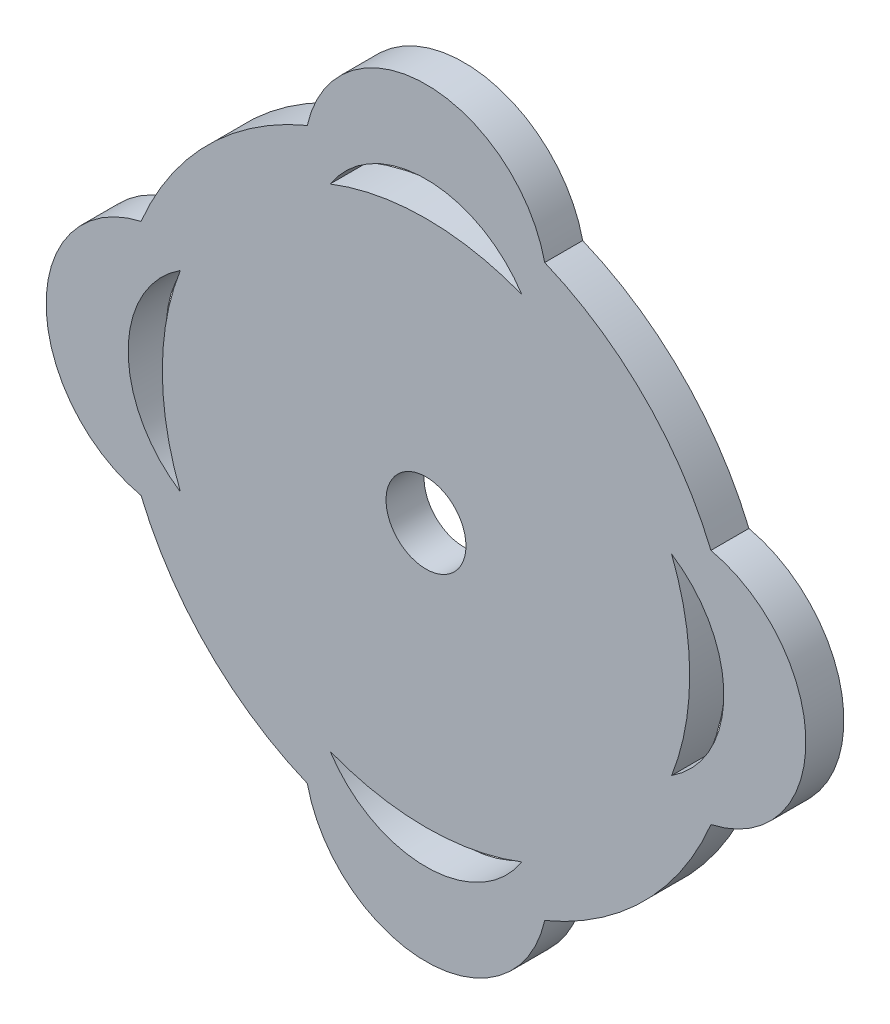
SolidWorks part; units mm, degrees
material "PLA"
ref_plane "Front Plane" through (0, 0, 0) normal (0, 0, 1) x (1, 0, 0)
ref_plane "Top Plane" through (0, 0, 0) normal (0, 1, 0) x (1, 0, 0)
ref_plane "Right Plane" through (0, 0, 0) normal (1, 0, 0) x (0, 0, -1)
sketch "Sketch1" plane through (0, 0, 0) normal (0, 0, 1) x (1, 0, 0)
  arc A0 (-3.175, -7.62) -> (3.175, -7.62) centre (0, -6.9056) ccw
  arc A1 (-7.62, 3.175) -> (-7.62, -3.175) centre (-6.9056, 0) ccw
  arc A2 (3.175, 7.62) -> (-3.175, 7.62) centre (0, 6.9056) ccw
  arc A6 (-7.62, 3.175) -> (-7.62, -3.175) centre (0, 0) ccw
  arc A7 (-7.62, 3.175) -> (-7.62, -3.175) centre (-6.9056, 0) ccw
  arc A8 (7.62, -3.175) -> (7.62, 3.175) centre (6.9056, 0) ccw
  arc A9 (-7.62, -3.175) -> (7.62, -3.175) centre (0, 0) ccw
  arc A10 (7.62, -3.175) -> (7.62, 3.175) centre (0, 0) ccw
  arc A11 (7.62, 3.175) -> (-7.62, 3.175) centre (0, 0) ccw
  point P26 (0, 0)
  dimension "D1" = 4
extrude "Boss-Extrude1" add sketch "Sketch1" along normal blind 1.016 contours A10 A8 | A10 A11 A6 A9 | A6 A7 | A11 A2 | A9 A0
scale "Scale1" bodies to scale 102 scale about centroid uniform scaling yes scale factor 1.04
sketch "Sketch2" plane through (0, 0, 1.0363) normal (0, 0, 1) x (1, 0, 0)
  circle A0 centre (0, 0) radius 1.1112
  dimension "D1" = 2.2225
extrude "Needle Cut" cut sketch "Sketch2" against normal through all
sketch "Sketch3" plane through (0, 0, 1.0363) normal (0, 0, 1) x (1, 0, 0)
  circle A3 centre (0, 0) radius 7.3343
  arc A4 (6.8322, 2.667) -> (6.8322, -2.667) centre (5.1094, 0) cw
  arc A5 (-6.8322, 2.667) -> (-6.8322, -2.667) centre (-5.1094, 0) ccw
  arc A6 (2.667, -6.8322) -> (-2.667, -6.8322) centre (0, -5.1094) cw
  arc A7 (-6.8322, -2.667) -> (-6.8322, 2.667) centre (-5.1094, 0) cw
  arc A8 (-2.667, 6.8322) -> (2.667, 6.8322) centre (0, 5.1094) cw
  point P30 (0, 0)
  dimension "D2" = 3.175
  dimension "D3" = 5.334
  dimension "D4" = 4
extrude "Tab Cut" cut sketch "Sketch3" against normal through all contours A8 A3 | A4 A3 | A6 A3 | A3 A5
